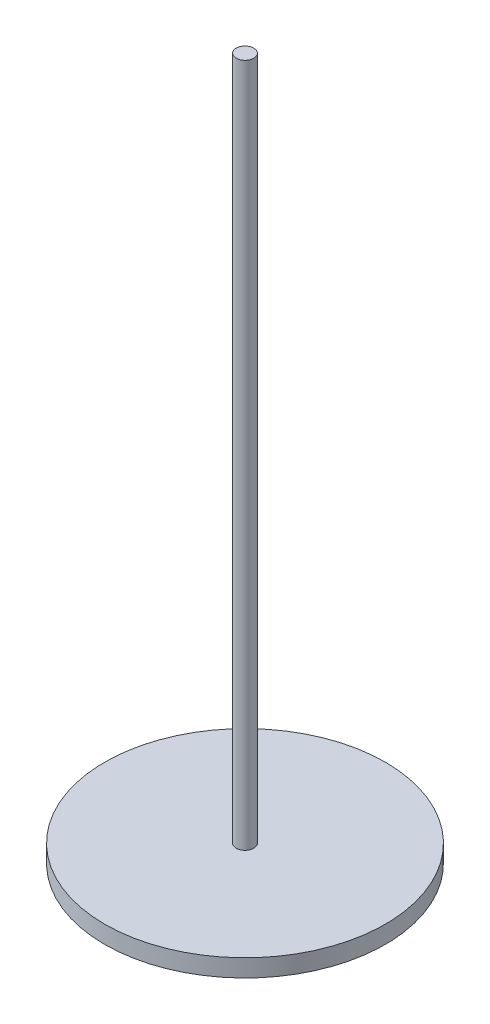
SolidWorks part; units mm, degrees
ref_plane "Front Plane" through (0, 0, 0) normal (0, 0, 1) x (1, 0, 0)
ref_plane "Top Plane" through (0, 0, 0) normal (0, 1, 0) x (1, 0, 0)
ref_plane "Right Plane" through (0, 0, 0) normal (1, 0, 0) x (0, 0, -1)
sketch "Sketch1" plane through (0, 0, 0) normal (1, 0, 0) x (0, 0, -1)
  line L0 (0, -619.1011) -> (0, 30335.9529) construction
  line L1 (-1.25, 76.5845) -> (-1.25, -20.9155)
  line L2 (-1.25, -20.9155) -> (-20, -20.9155)
  line L3 (-20, -20.9155) -> (-20, -23.4155)
  line L4 (-20, -23.4155) -> (0, -23.4155)
  line L5 (-1.25, 76.5845) -> (0, 76.5845)
  line L6 (0, 76.5845) -> (0, -23.4155)
  dimension "D1" = 100
  dimension "D2" = 20
  dimension "D3" = 2.5
  dimension "D4" = 1.25
revolve "Revolve1" add sketch "Sketch1" angle 360 about L6
